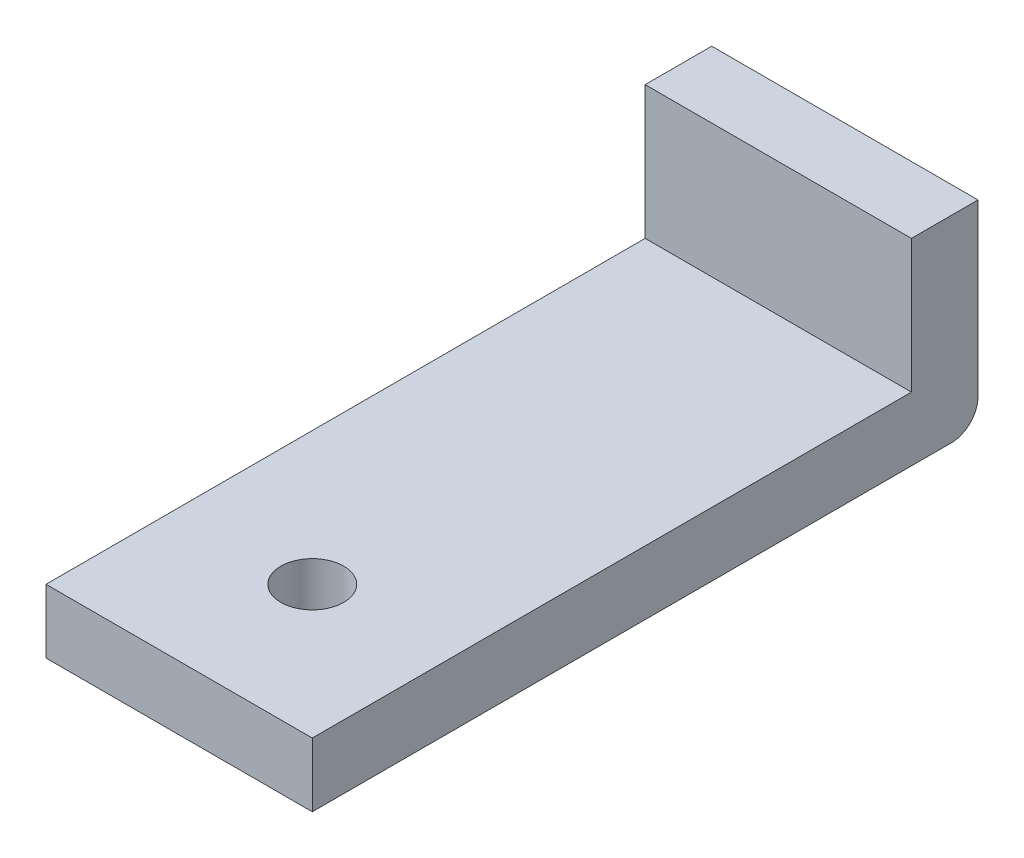
SolidWorks part; units mm, degrees
ref_plane "Front Plane" through (0, 0, 0) normal (0, 0, 1) x (1, 0, 0)
ref_plane "Top Plane" through (0, 0, 0) normal (0, 1, 0) x (1, 0, 0)
ref_plane "Right Plane" through (0, 0, 0) normal (1, 0, 0) x (0, 0, -1)
sketch "Sketch1" plane through (0, 0, 0) normal (1, 0, 0) x (0, 0, -1)
  line L0 (-15.875, 0) -> (15.875, 0)
  line L1 (15.875, 0) -> (15.875, 9.398)
  line L2 (15.875, 9.398) -> (12.7, 9.398)
  line L3 (12.7, 9.398) -> (12.7, 3.048)
  line L4 (12.7, 3.048) -> (-15.875, 3.048)
  line L5 (-15.875, 3.048) -> (-15.875, 0)
  point P5 (0, 0)
  point P8 (-9.525, 3.048)
  point P9 (-22.367, 0)
  point P10 (0, 0)
  dimension "D1" = 3.175
  dimension "D2" = 3.048
  dimension "D3" = 6.35
  dimension "D4" = 22.225
  dimension "D5" = 6.35
extrude "Boss-Extrude1" add sketch "Sketch1" along normal mid plane 12.7
sketch "Sketch4" plane through (0, 3.048, 0) normal (0, 1, 0) x (1, 0, 0)
  circle A0 centre (0, -9.525) radius 1.5
  dimension "D1" = 3
extrude "Cut-Extrude1" cut sketch "Sketch4" against normal through all
fillet "Fillet1" radius 1.27 1 edges at (0, 0, -15.875)
equation "\"WallThickness\"=0.125"
equation "\"D4@Sketch1\"=\"WallThickness\"+.75"
